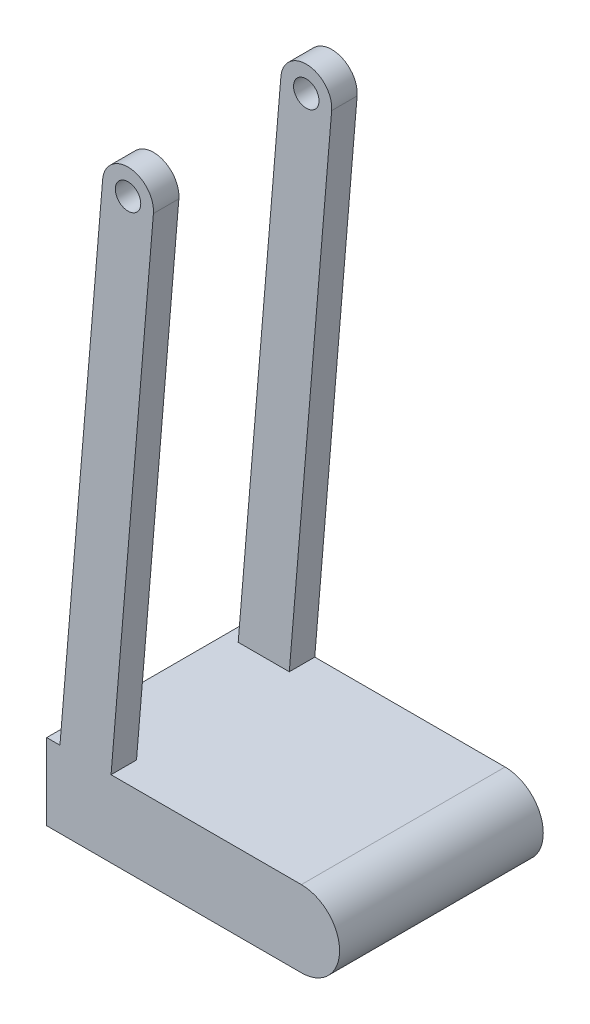
SolidWorks part; units mm, degrees
ref_plane "前基準面" through (0, 0, 0) normal (0, 0, 1) x (1, 0, 0)
ref_plane "上基準面" through (0, 0, 0) normal (0, 1, 0) x (1, 0, 0)
ref_plane "右基準面" through (0, 0, 0) normal (1, 0, 0) x (0, 0, -1)
sketch "草圖1" plane through (0, 0, 0) normal (0, 0, 1) x (1, 0, 0)
  line L0 (0.5192, 3) -> (2.1964, 23.0832)
  line L1 (4.1895, 22.9168) -> (2.5261, 3)
  line L2 (2.5261, 3) -> (10, 3)
  line L3 (10, 0) -> (0, 0)
  line L4 (0.5192, 3) -> (0, 3)
  line L5 (0, 3) -> (0, 0)
  arc A0 (2.1964, 23.0832) -> (4.1895, 22.9168) centre (3.193, 23) cw
  arc A1 (10, 3) -> (10, 0) centre (10, 1.5) cw
  circle A2 centre (3.193, 23) radius 0.5
  dimension "D1" = 1
  dimension "D2" = 1
  dimension "D3" = 3
  dimension "D4" = 10
  dimension "D5" = 20
extrude "填料-伸長1" add sketch "草圖1" along normal blind 8
sketch "草圖2" plane through (0, 0, 0) normal (-1, 0, 0) x (0, 0, 1)
  line L0 (8, 3) -> (0, 3) construction
  line L1 (1, 3) -> (7, 3)
  line L2 (1, 3) -> (1, 24)
  line L3 (1, 24) -> (7, 24)
  line L4 (7, 3) -> (7, 24)
  line L5 (8, 24) -> (0, 24) construction
  line L6 (0, 23.0832) -> (0, 3) construction
  line L7 (8, 23.0832) -> (8, 3) construction
  dimension "D1" = 1
  dimension "D2" = 1
extrude "除料-伸長1" cut sketch "草圖2" against normal blind 7
